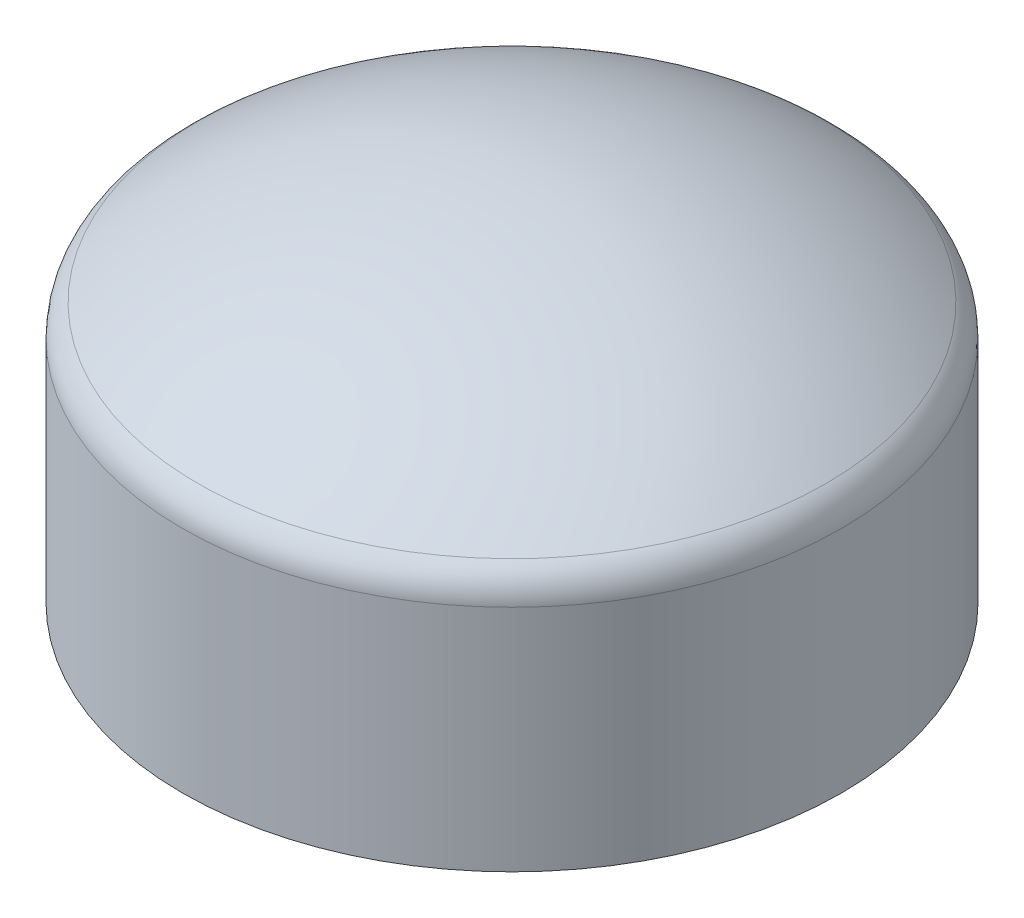
SolidWorks part; units mm, degrees
material "ABS"
ref_plane "Front Plane" through (0, 0, 0) normal (0, 0, 1) x (1, 0, 0)
ref_plane "Top Plane" through (0, 0, 0) normal (0, 1, 0) x (1, 0, 0)
ref_plane "Right Plane" through (0, 0, 0) normal (1, 0, 0) x (0, 0, -1)
sketch "Sketch1" plane through (0, 0, 0) normal (0, 0, 1) x (1, 0, 0)
  line L0 (-6.5, 0) -> (-8.5, 0)
  line L1 (-6.5, 0) -> (6.5, 0) construction
  line L2 (-6.5, 0) -> (-6.5, 5.4)
  line L3 (-6.5, 5.4) -> (0, 5.4)
  line L5 (-8.5, 0) -> (-8.5, 6.4)
  line L6 (0, 5.4) -> (0, 9.4)
  line L7 (0, 9.4) -> (2.3573, 9.4) construction
  arc A0 (-8.5, 6.4) -> (0, 9.4) centre (0, -4.1417) cw
  point P1 (-8.5, 5.4)
  point P10 (-8.5, 6.257)
  point P12 (-8.5, 6.3919)
  dimension "D3" = 2
  dimension "D1" = 5.4
  dimension "D2" = 13
  dimension "D4" = 4
  dimension "D5" = 1
revolve "Revolve1" add sketch "Sketch1" angle 360 about L6
fillet "Fillet1" radius 1 1 edges at (8.5, 6.4, 0)
